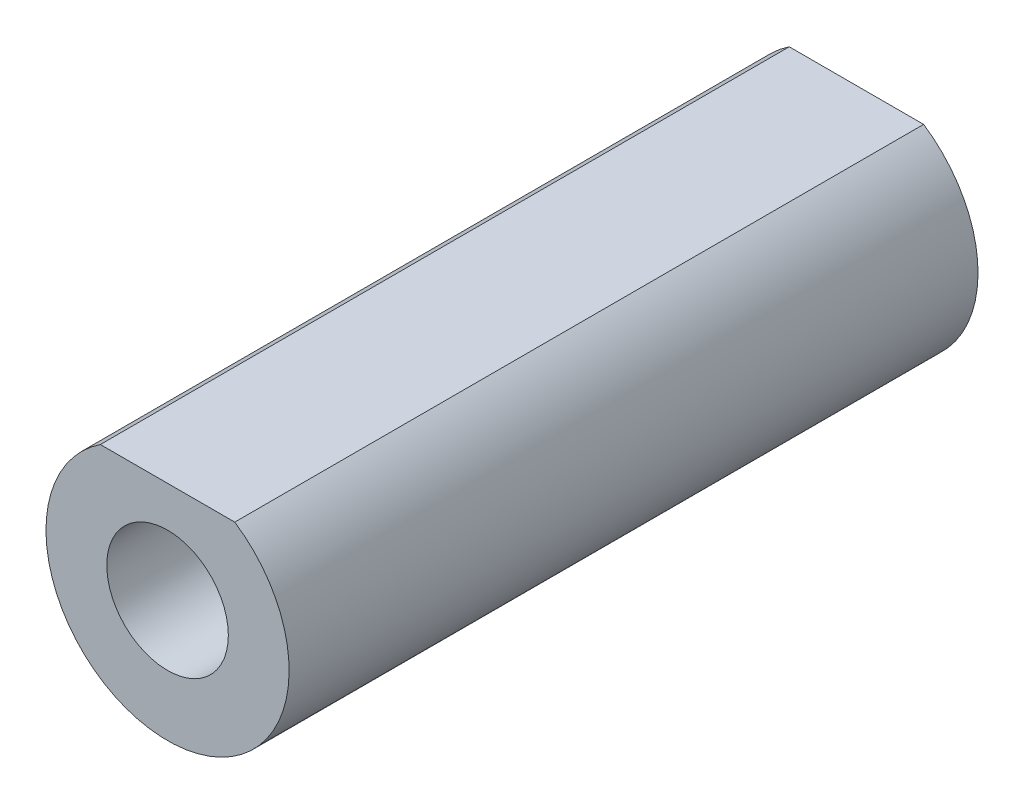
SolidWorks part; units mm, degrees
ref_plane "前视基准面" through (0, 0, 0) normal (0, 0, 1) x (1, 0, 0)
ref_plane "上视基准面" through (0, 0, 0) normal (0, 1, 0) x (1, 0, 0)
ref_plane "右视基准面" through (0, 0, 0) normal (1, 0, 0) x (0, 0, -1)
sketch "草图1" plane through (0, 0, 0) normal (0, 0, 1) x (1, 0, 0)
  line L1 (0, 5) -> (3.3166, 5)
  line L2 (0, 5) -> (-3.3166, 5)
  circle A0 centre (0, 0) radius 3
  arc A1 (-3.3166, 5) -> (3.3166, 5) centre (0, 0) ccw
extrude "凸台-拉伸1" add sketch "草图1" along normal blind 34
